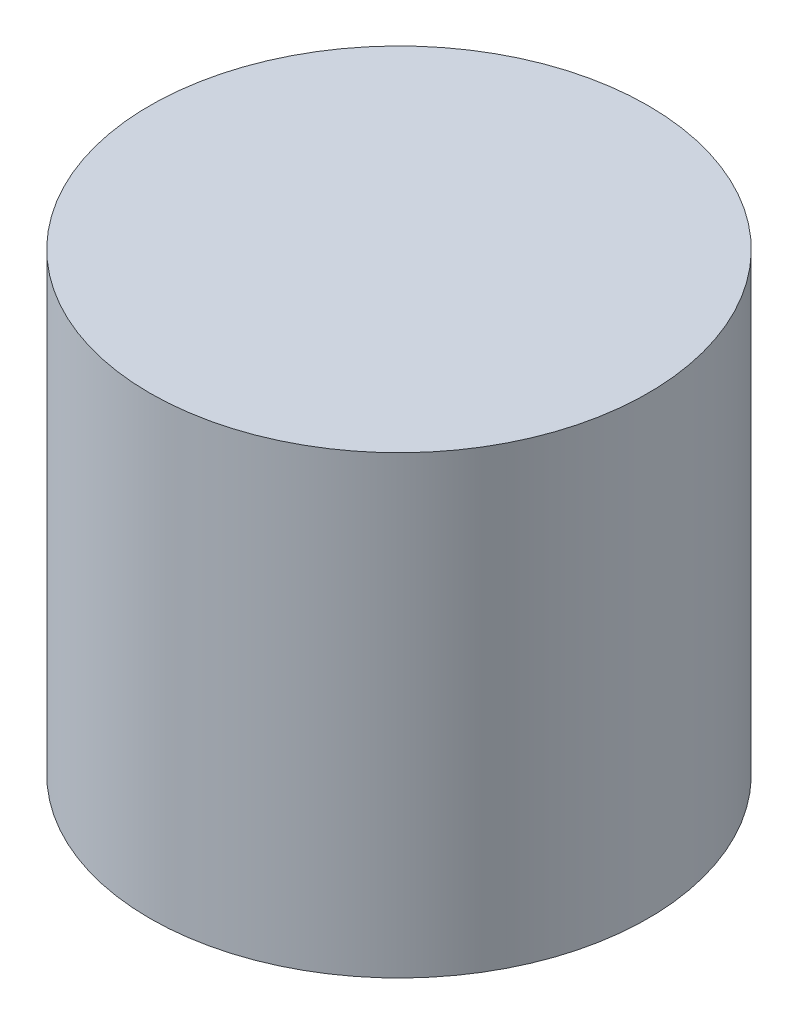
SolidWorks part; units mm, degrees
ref_plane "Front Plane" through (0, 0, 0) normal (0, 0, 1) x (1, 0, 0)
ref_plane "Top Plane" through (0, 0, 0) normal (0, 1, 0) x (1, 0, 0)
ref_plane "Right Plane" through (0, 0, 0) normal (1, 0, 0) x (0, 0, -1)
sketch "Sketch1" plane through (0, 0, 0) normal (0, 1, 0) x (1, 0, 0)
  circle A0 centre (0, 0) radius 24.75
  dimension "D1" = 49.5
extrude "Boss-Extrude1" add sketch "Sketch1" along normal blind 45.2
